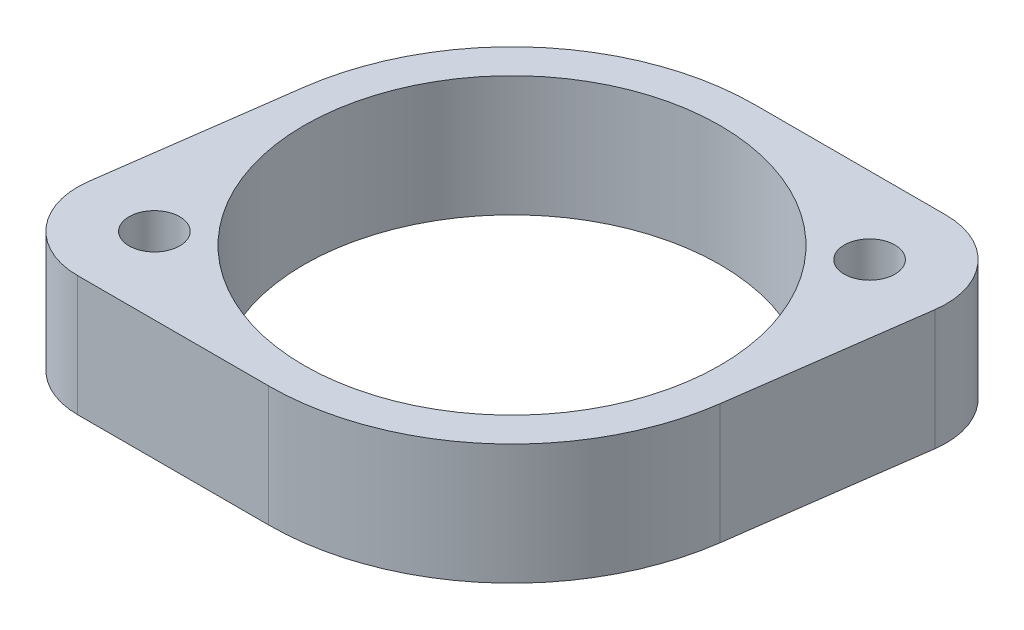
SolidWorks part; units mm, degrees
ref_plane "Front Plane" through (0, 0, 0) normal (0, 0, 1) x (1, 0, 0)
ref_plane "Top Plane" through (0, 0, 0) normal (0, 1, 0) x (1, 0, 0)
ref_plane "Right Plane" through (0, 0, 0) normal (1, 0, 0) x (0, 0, -1)
sketch "Sketch1" plane through (0, 0, 0) normal (0, 1, 0) x (1, 0, 0)
  line B0 (-29.2758, -17.1092) -> (-26.421, 3.6358)
  line B1 (0, -26.67) -> (-20.9406, -26.67)
  line B2 (29.2758, 17.1092) -> (26.421, -3.6358)
  line B3 (0, 26.67) -> (20.9406, 26.67)
  circle B4 centre (20.9406, 18.2563) radius 2.7781
  circle B5 centre (-20.9406, -18.2563) radius 2.7781
  circle B6 centre (0, 0) radius 22.7878
  arc B7 (0, 26.67) -> (-26.421, 3.6358) centre (0, 0) ccw
  arc B8 (-29.2758, -17.1092) -> (-20.9406, -26.67) centre (-20.9406, -18.2563) ccw
  arc B9 (0, -26.67) -> (26.421, -3.6358) centre (0, 0) ccw
  arc B10 (29.2758, 17.1092) -> (20.9406, 26.67) centre (20.9406, 18.2563) ccw
sketch_block_instance "Block1-1"
sketch_block "Block1"
extrude "Boss-Extrude1" add sketch "Sketch1" along normal blind 13.208
